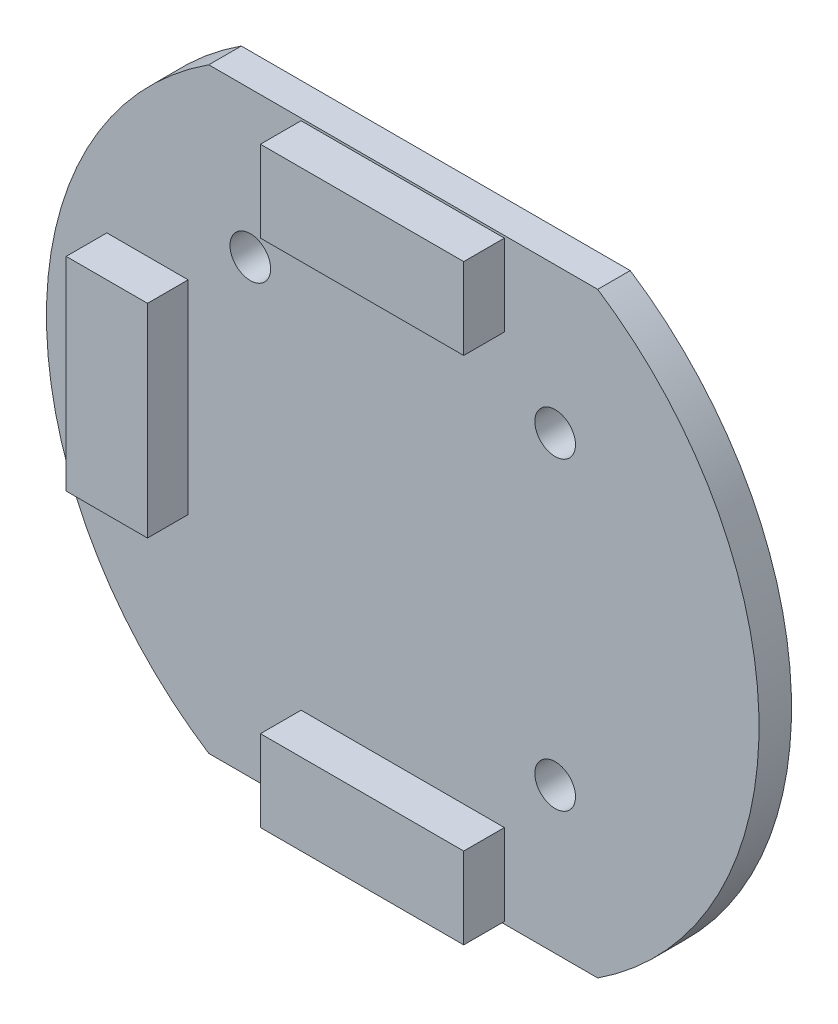
SolidWorks part; units mm, degrees
ref_plane "前视基准面" through (0, 0, 0) normal (0, 0, 1) x (1, 0, 0)
ref_plane "上视基准面" through (0, 0, 0) normal (0, 1, 0) x (1, 0, 0)
ref_plane "右视基准面" through (0, 0, 0) normal (1, 0, 0) x (0, 0, -1)
sketch "草图1" plane through (0, 0, 0) normal (0, 0, 1) x (1, 0, 0)
  line L0 (-9.5416, 14.6685) -> (9.5914, 14.6685)
  line L1 (-17.526, 14.6685) -> (17.526, 14.6685) construction
  line L2 (-17.526, 14.6685) -> (-17.526, -14.6685) construction
  line L3 (-17.526, -14.6685) -> (17.526, -14.6685) construction
  line L4 (17.526, 14.6685) -> (17.526, -14.6685) construction
  line L5 (9.5914, -14.6685) -> (-9.5416, -14.6685)
  line L6 (0, 0) -> (0, -33.5817) construction
  line L7 (0, 0) -> (30.8589, -30.8589) construction
  circle A0 centre (0, 0) radius 10.6045 construction
  circle A1 centre (0, 0) radius 17.526 construction
  arc A7 (-9.5416, 14.6685) -> (-9.5416, -14.6685) centre (-0.0598, 0) ccw
  arc A8 (9.5914, 14.6685) -> (9.5914, -14.6685) centre (0, 0) cw
  circle A13 centre (7.4985, -7.4985) radius 1
  circle A15 centre (-7.4985, 7.4985) radius 1
  circle A16 centre (7.4985, 7.4985) radius 1
  circle A17 centre (-7.4985, -7.4985) radius 1 [skipped]
  dimension "D1" = 21.209
  dimension "D2" = 4
  dimension "D3" = 35.052
  dimension "D4" = 29.337
  dimension "D5" = 14.6685
  dimension "D6" = 35.052
  dimension "D7" = 17.526
  dimension "D8" = 45
extrude "凸台-拉伸1" add sketch "草图1" along normal blind 1.6
sketch "草图2" plane through (0, 0, 0) normal (0, 0, -1) x (-1, 0, 0)
  line L1 (-0.8887, 1.814) -> (0.8887, 1.814)
  line L2 (-0.8887, 1.814) -> (-0.8887, -1.814)
  line L3 (-0.8887, -1.814) -> (0.8887, -1.814)
  line L4 (0.8887, 1.814) -> (0.8887, -1.814)
  line L5 (-0.8887, 1.814) -> (0.8887, -1.814) construction
  line L6 (-0.8887, -1.814) -> (0.8887, 1.814) construction
  point P0 (0, 0)
extrude "凸台-拉伸2" add sketch "草图2" along normal blind 1.7
sketch "草图3" plane through (0, 0, 1.6) normal (0, 0, 1) x (1, 0, 0)
  line L0 (-10.5555, 5) -> (-14.5555, 5)
  line L1 (-5, -10.5555) -> (5, -10.5555)
  line L2 (-5, -10.5555) -> (-5, -14.5555)
  line L3 (-5, -14.5555) -> (5, -14.5555)
  line L4 (5, -10.5555) -> (5, -14.5555)
  line L5 (-10.5555, 5) -> (-10.5555, -5)
  line L6 (-10.5555, -5) -> (-14.5555, -5)
  line L7 (-14.5555, 5) -> (-14.5555, -5)
  line L8 (5, 10.5555) -> (5, 14.5555)
  line L9 (5, 10.5555) -> (-5, 10.5555)
  line L10 (-5, 10.5555) -> (-5, 14.5555)
  line L11 (5, 14.5555) -> (-5, 14.5555)
  line L16 (14.5555, -5) -> (14.5555, 5) [skipped]
  line L17 (10.5555, -5) -> (10.5555, 5) [skipped]
  line L18 (10.5555, 5) -> (14.5555, 5) [skipped]
  line L19 (10.5555, -5) -> (14.5555, -5) [skipped]
  dimension "D1" = 10
  dimension "D2" = 4
  dimension "D3" = 4
extrude "凸台-拉伸3" add sketch "草图3" along normal blind 2
